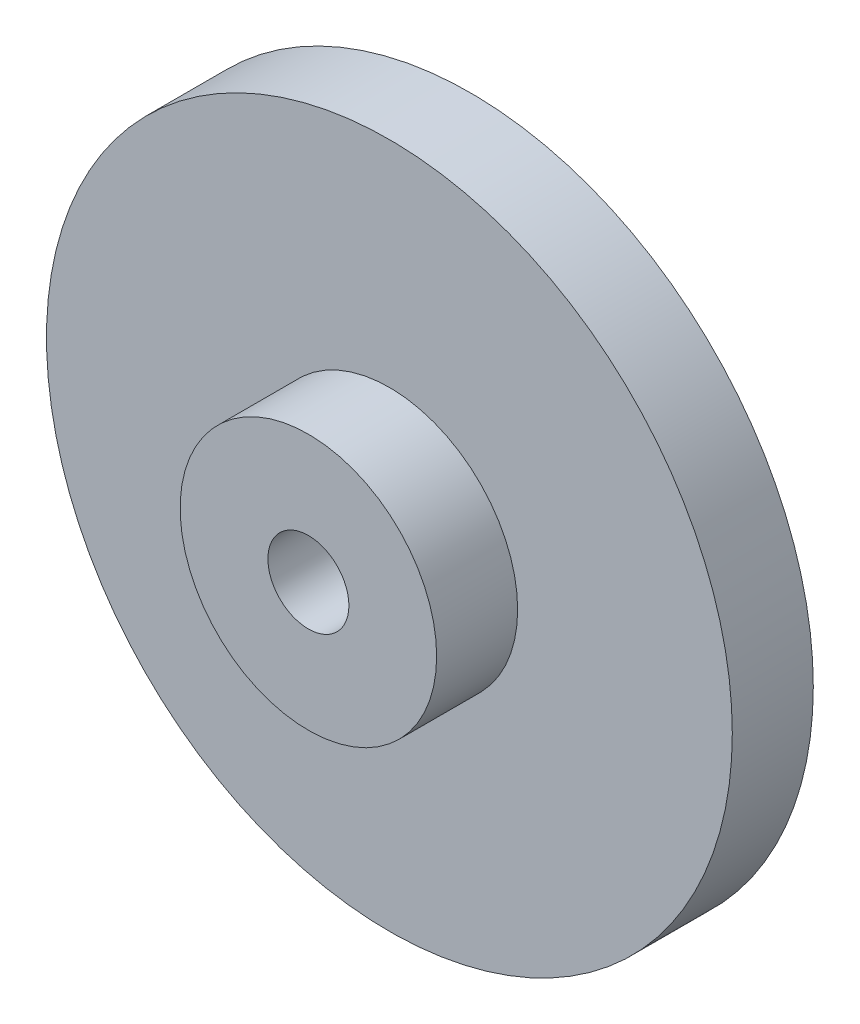
SolidWorks part; units mm, degrees
material "PET 90%"
ref_plane "Front Plane" through (0, 0, 0) normal (0, 0, 1) x (1, 0, 0)
ref_plane "Top Plane" through (0, 0, 0) normal (0, 1, 0) x (1, 0, 0)
ref_plane "Right Plane" through (0, 0, 0) normal (1, 0, 0) x (0, 0, -1)
sketch "Sketch1" plane through (0, 0, 0) normal (0, 0, 1) x (1, 0, 0)
  circle A0 centre (0, 0) radius 25.4
  dimension "D1" = 50.8
extrude "Boss-Extrude1" add sketch "Sketch1" along normal blind 6
sketch "Sketch4" plane through (0, 0, 6) normal (0, 0, 1) x (1, 0, 0)
  circle A0 centre (0, 0) radius 9.5
  dimension "D1" = 19
extrude "Boss-Extrude2" add sketch "Sketch4" along normal blind 6
sketch "Sketch6" plane through (0, 0, 0) normal (0, 0, 1) x (1, 0, 0)
  circle A0 centre (0, 0) radius 3
  dimension "D1" = 6
extrude "Cut-Extrude1" cut sketch "Sketch6" along normal up to next
